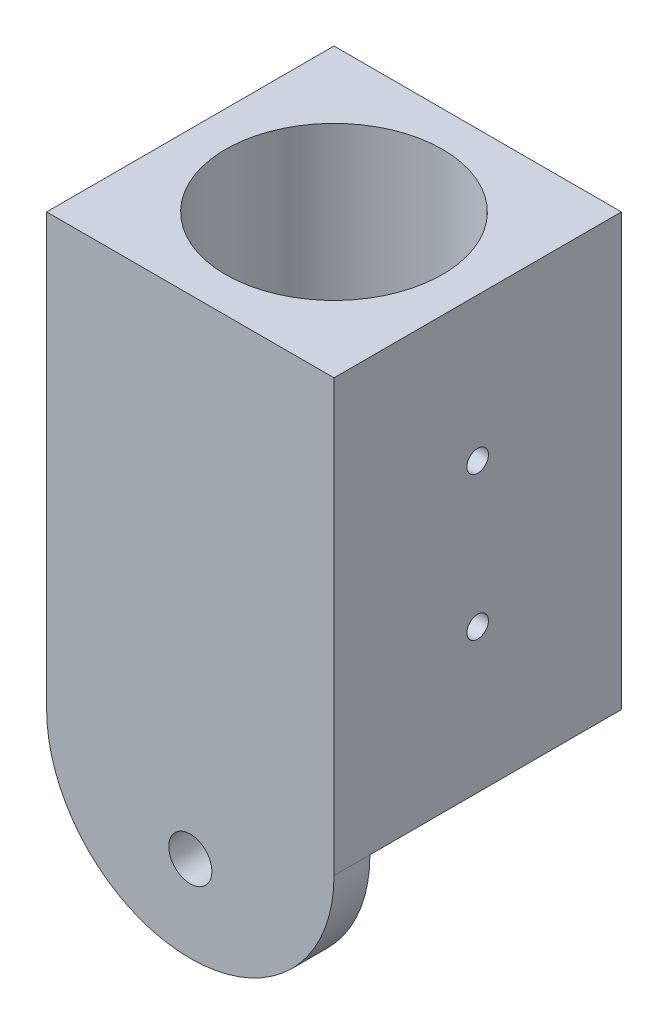
SolidWorks part; units mm, degrees
ref_plane "前基準面" through (0, 0, 0) normal (0, 0, 1) x (1, 0, 0)
ref_plane "上基準面" through (0, 0, 0) normal (0, 1, 0) x (1, 0, 0)
ref_plane "右基準面" through (0, 0, 0) normal (1, 0, 0) x (0, 0, -1)
sketch "草圖1" plane through (0, 0, 0) normal (0, 1, 0) x (1, 0, 0)
  line L1 (-20, 20) -> (20, 20)
  line L2 (-20, 20) -> (-20, -20)
  line L3 (-20, -20) -> (20, -20)
  line L4 (20, 20) -> (20, -20)
  line L5 (-20, 20) -> (20, -20) construction
  line L6 (-20, -20) -> (20, 20) construction
  dimension "D2" = 40
extrude "填料-伸長1" add sketch "草圖1" along normal blind 60
sketch "草圖2" plane through (0, 60, 0) normal (0, 1, 0) x (1, 0, 0)
  circle A0 centre (0, 0) radius 15.1
  dimension "D1" = 30.2
extrude "除料-伸長1" cut sketch "草圖2" against normal blind 50
sketch "草圖3" plane through (0, 0, 20) normal (0, 0, 1) x (1, 0, 0)
  line L0 (-20, 0) -> (20, 0) construction
  line L1 (-20, 0) -> (20, 0)
  arc A0 (-20, 0) -> (20, 0) centre (0, 0) ccw
  circle A1 centre (0, -8) radius 3
  dimension "D1" = 6
  dimension "D2" = 8
extrude "填料-伸長2" add sketch "草圖3" against normal blind 5
sketch "草圖4" plane through (20, 0, 0) normal (1, 0, 0) x (0, 0, -1)
  circle A0 centre (0, 20) radius 1.5
  dimension "D1" = 3
  dimension "D2" = 20
extrude "除料-伸長2" cut sketch "草圖4" against normal through all
pattern_linear "直線複製排列1" count 2 spacing 20 along (0, 1, 0) of "除料-伸長2"
